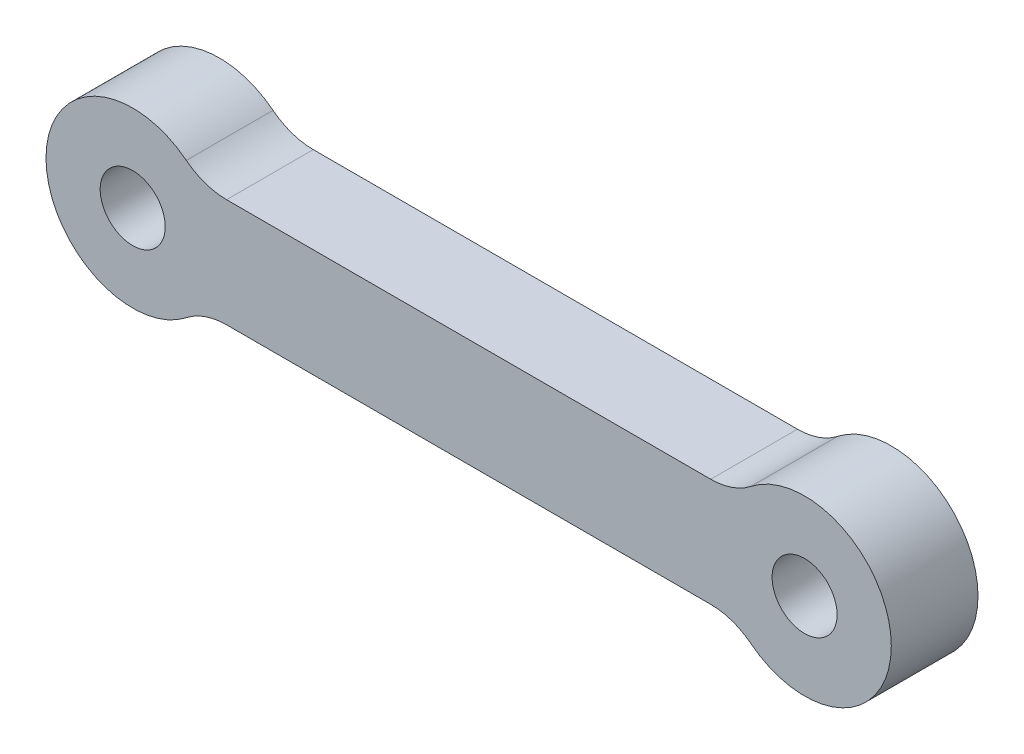
SolidWorks part; units mm, degrees
ref_plane "Front Plane" through (0, 0, 0) normal (0, 0, 1) x (1, 0, 0)
ref_plane "Top Plane" through (0, 0, 0) normal (0, 1, 0) x (1, 0, 0)
ref_plane "Right Plane" through (0, 0, 0) normal (1, 0, 0) x (0, 0, -1)
sketch "Sketch1" plane through (0, 0, 0) normal (0, 0, 1) x (1, 0, 0)
  line L0 (-15.5, 0) -> (15.5, 0) construction
  line L1 (0, 0) -> (0, 3.513)
  line L3 (-11.1699, 2.5) -> (11.1699, 2.5)
  line L5 (-11.1699, -2.5) -> (11.1699, -2.5)
  line L7 (-12.3775, 2.5) -> (12.3775, -2.5) construction
  line L8 (-12.3775, -2.5) -> (12.3775, 2.5) construction
  circle A0 centre (-15.5, 0) radius 1.5
  arc A1 (-13.0256, 3.1429) -> (-13.0256, -3.1429) centre (-15.5, 0) ccw
  circle A2 centre (15.5, 0) radius 1.5
  arc A3 (13.0256, 3.1429) -> (13.0256, -3.1429) centre (15.5, 0) cw
  arc A4 (11.1699, -2.5) -> (13.0256, -3.1429) centre (11.1699, -5.5) cw
  arc A5 (11.1699, 2.5) -> (13.0256, 3.1429) centre (11.1699, 5.5) ccw
  arc A6 (-13.0256, -3.1429) -> (-11.1699, -2.5) centre (-11.1699, -5.5) cw
  arc A7 (-11.1699, 2.5) -> (-13.0256, 3.1429) centre (-11.1699, 5.5) cw
  point P4 (0, 0)
  dimension "D2" = 8
  dimension "D3" = 3
  dimension "D5" = 3
  dimension "D1" = 31
  dimension "D4" = 5
extrude "Boss-Extrude1" add sketch "Sketch1" along normal blind 4
